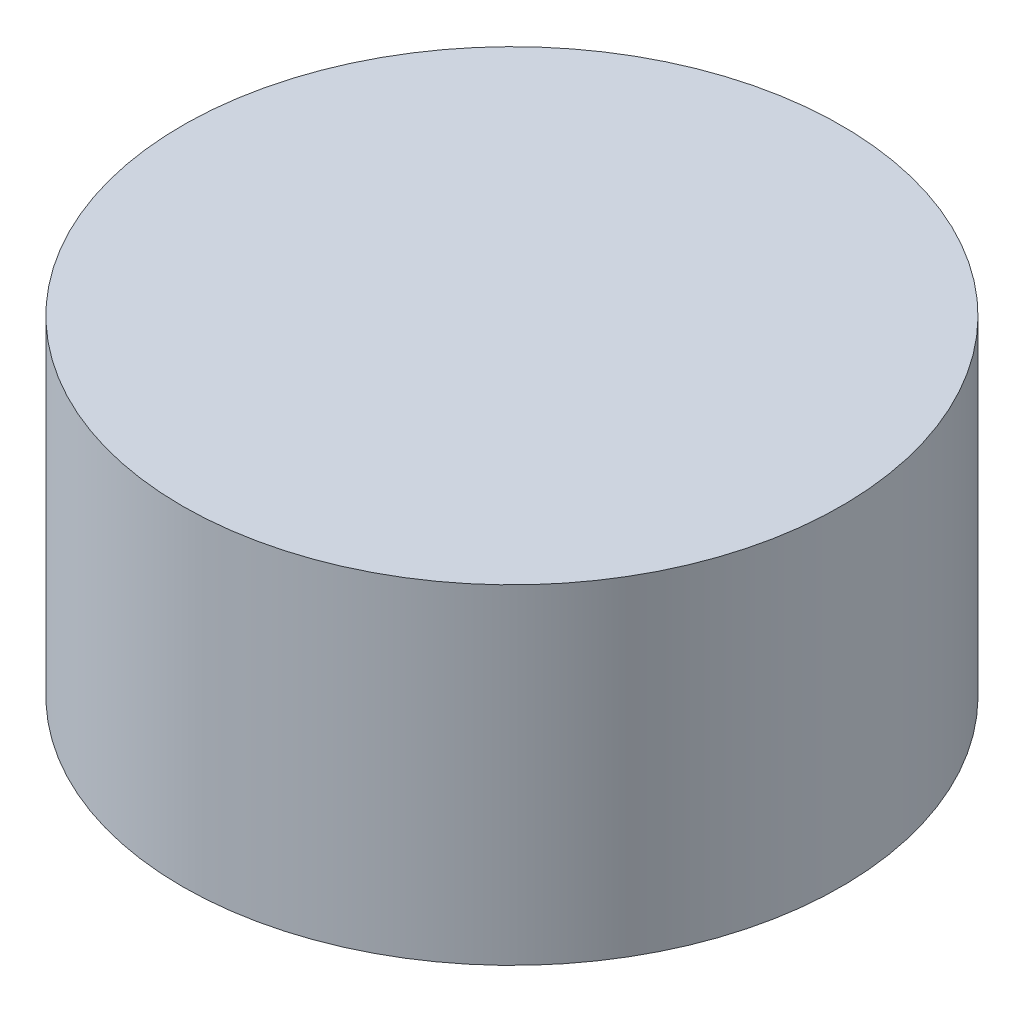
SolidWorks part; units mm, degrees
material "Nickel"
ref_plane "Front Plane" through (0, 0, 0) normal (0, 0, 1) x (1, 0, 0)
ref_plane "Top Plane" through (0, 0, 0) normal (0, 1, 0) x (1, 0, 0)
ref_plane "Right Plane" through (0, 0, 0) normal (1, 0, 0) x (0, 0, -1)
sketch "Sketch1" plane through (0, 0, 0) normal (0, 1, 0) x (1, 0, 0)
  circle A0 centre (0, 0) radius 3.175
  dimension "D1" = 6.35
extrude "Boss-Extrude1" add sketch "Sketch1" along normal blind 3.175
